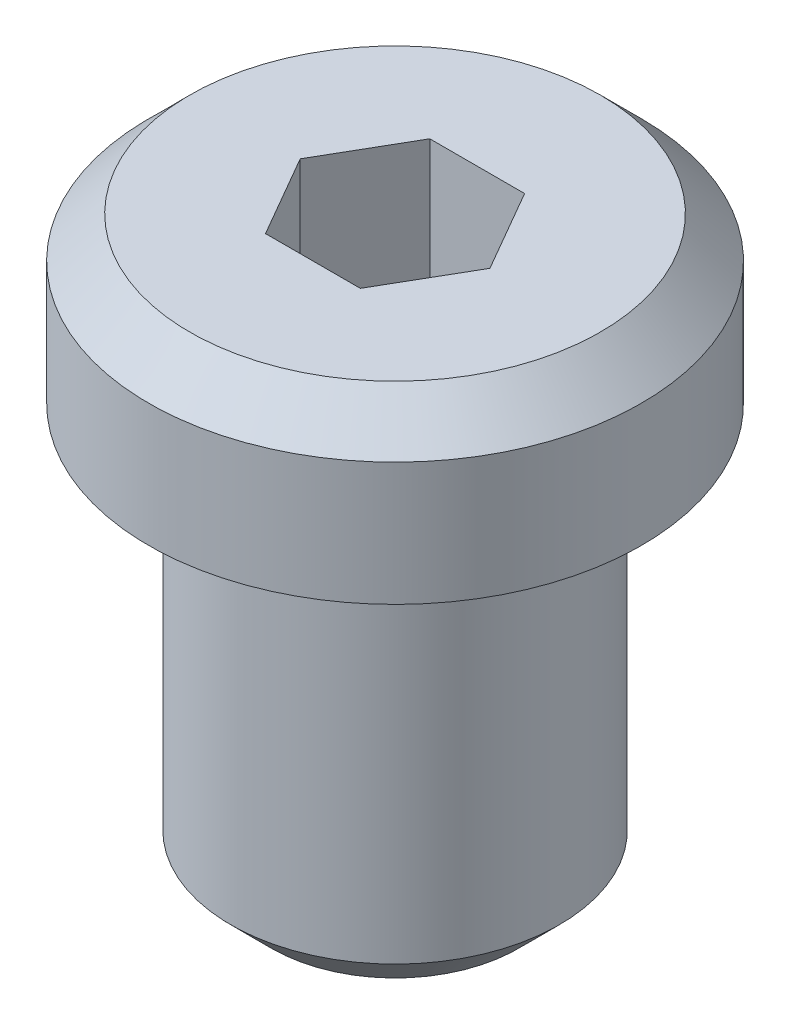
SolidWorks part; units mm, degrees
ref_plane "Alzado" through (0, 0, 0) normal (0, 0, 1) x (1, 0, 0)
ref_plane "Planta" through (0, 0, 0) normal (0, 1, 0) x (1, 0, 0)
ref_plane "Vista lateral" through (0, 0, 0) normal (1, 0, 0) x (0, 0, -1)
sketch "Croquis2" plane through (0, 0, 0) normal (0, 0, 1) x (1, 0, 0)
  line L0 (0, 0) -> (0, 14)
  line L1 (0, 14) -> (5, 14)
  line L2 (5, 14) -> (6, 13)
  line L3 (6, 13) -> (6, 10)
  line L4 (6, 10) -> (4, 10)
  line L5 (4, 10) -> (4, 1)
  line L6 (4, 1) -> (3, 0)
  line L7 (3, 0) -> (0, 0)
  dimension "D1" = 14
  dimension "D2" = 4
  dimension "D3" = 1
  dimension "D4" = 45
  dimension "D5" = 1
  dimension "D6" = 4
  dimension "D7" = 6
revolve "Revolución1" add sketch "Croquis2" angle 360 about L0
sketch "Croquis3" plane through (0, 14, 0) normal (0, 1, 0) x (1, 0, 0)
  line L1 (1.1547, 2) -> (-1.1547, 2)
  line L2 (-1.1547, 2) -> (-2.3094, 0)
  line L3 (-2.3094, 0) -> (-1.1547, -2)
  line L4 (-1.1547, -2) -> (1.1547, -2)
  line L5 (1.1547, -2) -> (2.3094, 0)
  line L6 (2.3094, 0) -> (1.1547, 2)
  circle A0 centre (0, 0) radius 2 construction
  dimension "D1" = 4
extrude "Cortar-Extruir1" cut sketch "Croquis3" against normal blind 4
